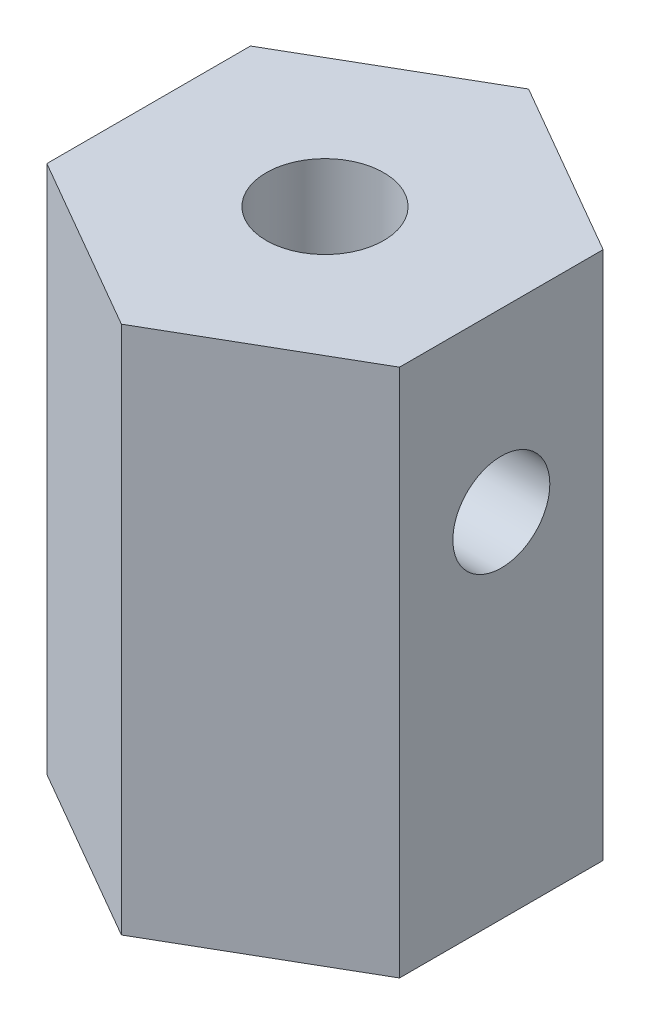
SolidWorks part; units mm, degrees
ref_plane "Plan de face" through (0, 0, 0) normal (0, 0, 1) x (1, 0, 0)
ref_plane "Plan de dessus" through (0, 0, 0) normal (0, 1, 0) x (1, 0, 0)
ref_plane "Plan de droite" through (0, 0, 0) normal (1, 0, 0) x (0, 0, -1)
sketch "Esquisse1" plane through (0, 0, 0) normal (0, 1, 0) x (1, 0, 0)
  line L0 (-6, -3.4641) -> (0, -6.9282)
  line L1 (6, 3.4641) -> (0, 6.9282)
  line L2 (0, 6.9282) -> (-6, 3.4641)
  line L3 (-6, 3.4641) -> (-6, -3.4641)
  line L4 (0, -6.9282) -> (6, -3.4641)
  line L5 (6, -3.4641) -> (6, 3.4641)
  circle A0 centre (0, 0) radius 6 construction
  dimension "D1" = 12
extrude "Boss.-Extru.1" add sketch "Esquisse1" along normal blind 18
sketch "Esquisse2" plane through (0, 18, 0) normal (0, 1, 0) x (1, 0, 0)
  circle A1 centre (0, 0) radius 2
  dimension "D1" = 4
extrude "Enlèv. mat.-Extru.1" cut sketch "Esquisse2" against normal blind 10
hole_wizard "Trou pour taraudage pour trou taraudé M4x0.71" positions "Esquisse3D1" profile "Esquisse4" hole size "M4x0.7" standard "Ansi Metric" end condition up to next
sketch3d "Esquisse3D1"
  point P5 (0, 0, 0)
sketch "Esquisse4" plane through (0, 0, 0) normal (1, 0, 0) x (0, 0, -1)
  line L0 (0, 0) -> (0, 8)
  line L1 (0, 8) -> (1.65, 8)
  line L2 (1.65, 8) -> (1.65, 0)
  line L5 (1.65, 0) -> (0, 0)
  line L11 (0, -6.35) -> (0, 107.95) construction
  dimension "Diamètre du perçage jusqu'au prochain" = 3.3
  dimension "Profondeur du perçage jusqu'au prochain" = 8
hole_wizard "Trou pour taraudage pour trou taraudé M4x0.72" positions "Esquisse5" profile "Esquisse6" hole size "M4x0.7" standard "Ansi Metric"
sketch "Esquisse5" plane through (6, 0, 0) normal (1, 0, 0) x (0, 0, -1)
  line L1 (2, 8) -> (-2, 8) construction
  point P0 (0, 12)
  dimension "D1" = 4
sketch "Esquisse6" plane through (6, 12, 0) normal (0, 1, 0) x (0, 0, -1)
  line L0 (0, 0) -> (0, 7)
  line L1 (0, 7) -> (1.65, 7)
  line L2 (1.65, 7) -> (1.65, 0)
  line L5 (1.65, 0) -> (0, 0)
  line L10 (0, 7) -> (-1.65, 7) construction
  line L11 (0, -6.35) -> (0, 107.95) construction
  dimension "Diamètre du perçage" = 3.3
  dimension "Profondeur du perçage" = 7
  dimension "Angle de pointe" = 180
